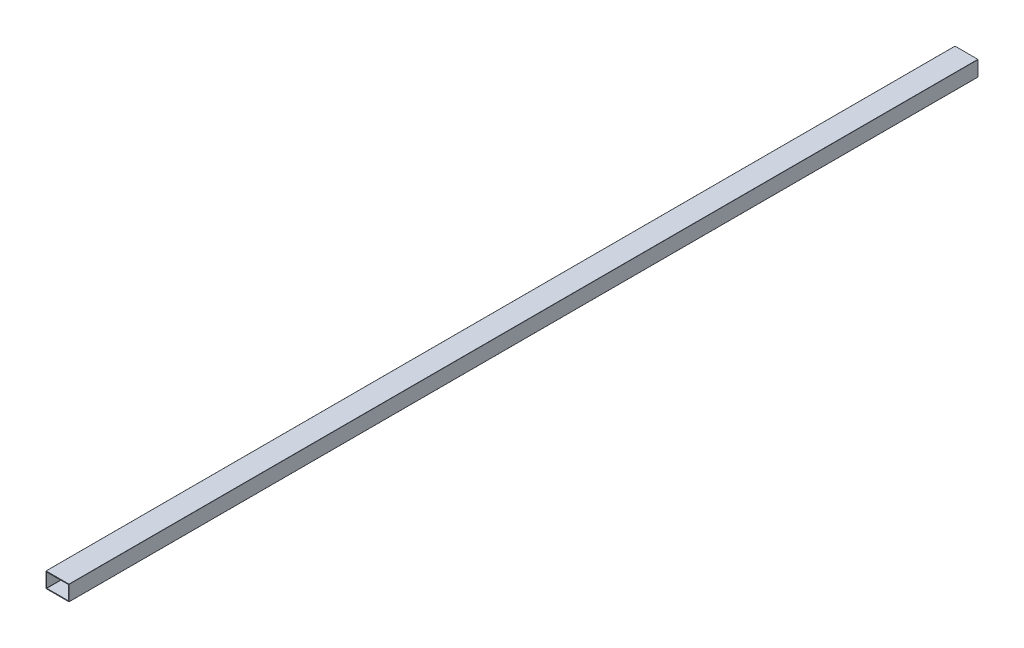
SolidWorks part; units mm, degrees
material "AISI 1035 Acero (SS)"
ref_plane "Alzado" through (0, 0, 0) normal (0, 0, 1) x (1, 0, 0)
ref_plane "Planta" through (0, 0, 0) normal (0, 1, 0) x (1, 0, 0)
ref_plane "Vista lateral" through (0, 0, 0) normal (1, 0, 0) x (0, 0, -1)
sketch "Croquis1" plane through (0, 0, 0) normal (0, 0, 1) x (1, 0, 0)
  line L0 (-71.65, -46.25) -> (-71.65, 46.25)
  line L1 (-76.2, -50.8) -> (76.2, -50.8)
  line L2 (-76.2, -50.8) -> (-76.2, 50.8)
  line L3 (-76.2, 50.8) -> (76.2, 50.8)
  line L4 (76.2, -50.8) -> (76.2, 50.8)
  line L5 (-76.2, -50.8) -> (76.2, 50.8) construction
  line L6 (-76.2, 50.8) -> (76.2, -50.8) construction
  line L7 (-71.65, 46.25) -> (71.65, 46.25)
  line L8 (71.65, -46.25) -> (71.65, 46.25)
  line L9 (-71.65, -46.25) -> (71.65, -46.25)
  point P0 (0, 0)
  dimension "D1" = 101.6
  dimension "D2" = 152.4
  dimension "D3" = 4.55
extrude "Saliente-Extruir1" add sketch "Croquis1" against normal blind 6000
fillet "Redondeo1" radius 1 8 edges at (-71.65, 46.25, -3000) (71.65, 46.25, -3000) (71.65, -46.25, -3000) (-76.2, -50.8, -3000) (-76.2, 50.8, -3000) (-71.65, -46.25, -3000) (76.2, -50.8, -3000) (76.2, 50.8, -3000)
